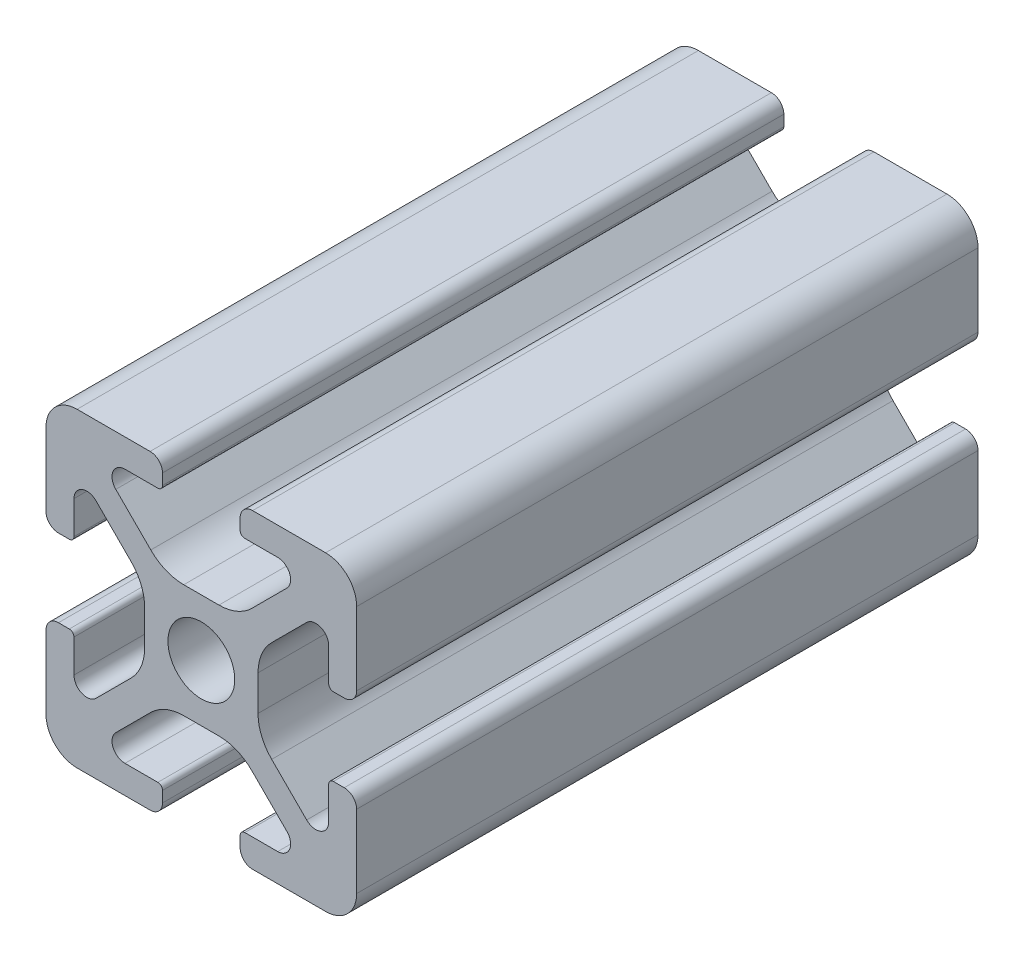
SolidWorks part; units mm, degrees
material "Alliage 1060"
ref_plane "Plan de face" through (0, 0, 0) normal (0, 0, 1) x (1, 0, 0)
ref_plane "Plan de dessus" through (0, 0, 0) normal (0, 1, 0) x (1, 0, 0)
ref_plane "Plan de droite" through (0, 0, 0) normal (1, 0, 0) x (0, 0, -1)
ref_plane "Plan1" through (0, 0, 0) normal (0, 0, -1) x (-1, 0, 0)
sketch "Esquisse1" plane through (0, 0, 0) normal (0, 0, -1) x (-1, 0, 0)
  line L0 (-18, 0) -> (-13.3, 0)
  line L1 (-12.8, 1.8) -> (-14.9184, 1.8)
  line L2 (-15.5064, 3.2196) -> (-13.2547, 5.4713)
  line L3 (-11.1334, 6.35) -> (-8.8666, 6.35)
  line L4 (-6.7453, 5.4713) -> (-4.4936, 3.2196)
  line L5 (-5.0816, 1.8) -> (-7.2, 1.8)
  line L6 (-6.7, 0) -> (-2, 0)
  line L7 (0, 2) -> (0, 6.7)
  line L8 (-1.8, 7.2) -> (-1.8, 5.0816)
  line L9 (-3.2196, 4.4936) -> (-5.4713, 6.7453)
  line L10 (-6.35, 8.8666) -> (-6.35, 11.1334)
  line L11 (-5.4713, 13.2547) -> (-3.2196, 15.5064)
  line L12 (-1.8, 14.9184) -> (-1.8, 12.8)
  line L13 (0, 13.3) -> (0, 18)
  line L14 (-2, 20) -> (-6.7, 20)
  line L15 (-7.2, 18.2) -> (-5.0816, 18.2)
  line L16 (-4.4936, 16.7804) -> (-6.7453, 14.5287)
  line L17 (-8.8666, 13.65) -> (-11.1334, 13.65)
  line L18 (-13.2547, 14.5287) -> (-15.5064, 16.7804)
  line L19 (-14.9184, 18.2) -> (-12.8, 18.2)
  line L20 (-13.3, 20) -> (-18, 20)
  line L21 (-20, 18) -> (-20, 13.3)
  line L22 (-16.7804, 15.5064) -> (-14.5287, 13.2547)
  line L23 (-13.65, 11.1334) -> (-13.65, 8.8666)
  line L24 (-14.5287, 6.7453) -> (-16.7804, 4.4936)
  line L25 (-18.2, 5.0816) -> (-18.2, 7.2)
  line L26 (-20, 6.7) -> (-20, 2)
  arc A0 (-20, 2) -> (-18, 0) centre (-18, 2) ccw
  arc A1 (-13.3, 0) -> (-12.5, 0.8) centre (-13.3, 0.8) ccw
  arc A2 (-12.5, 1.5) -> (-12.8, 1.8) centre (-12.8, 1.5) ccw
  arc A3 (-14.9184, 1.8) -> (-15.5064, 3.2196) centre (-14.9184, 2.6316) cw
  arc A4 (-13.2547, 5.4713) -> (-11.1334, 6.35) centre (-11.1334, 3.35) cw
  arc A5 (-8.8666, 6.35) -> (-6.7453, 5.4713) centre (-8.8666, 3.35) cw
  arc A6 (-4.4936, 3.2196) -> (-5.0816, 1.8) centre (-5.0816, 2.6316) cw
  arc A7 (-7.2, 1.8) -> (-7.5, 1.5) centre (-7.2, 1.5) ccw
  arc A8 (-7.5, 0.8) -> (-6.7, 0) centre (-6.7, 0.8) ccw
  arc A9 (-2, 0) -> (0, 2) centre (-2, 2) ccw
  arc A10 (0, 6.7) -> (-0.8, 7.5) centre (-0.8, 6.7) ccw
  arc A11 (-1.5, 7.5) -> (-1.8, 7.2) centre (-1.5, 7.2) ccw
  arc A12 (-1.8, 5.0816) -> (-3.2196, 4.4936) centre (-2.6316, 5.0816) cw
  arc A13 (-5.4713, 6.7453) -> (-6.35, 8.8666) centre (-3.35, 8.8666) cw
  arc A14 (-6.35, 11.1334) -> (-5.4713, 13.2547) centre (-3.35, 11.1334) cw
  arc A15 (-3.2196, 15.5064) -> (-1.8, 14.9184) centre (-2.6316, 14.9184) cw
  arc A16 (-1.8, 12.8) -> (-1.5, 12.5) centre (-1.5, 12.8) ccw
  arc A17 (-0.8, 12.5) -> (0, 13.3) centre (-0.8, 13.3) ccw
  arc A18 (0, 18) -> (-2, 20) centre (-2, 18) ccw
  arc A19 (-6.7, 20) -> (-7.5, 19.2) centre (-6.7, 19.2) ccw
  arc A20 (-7.5, 18.5) -> (-7.2, 18.2) centre (-7.2, 18.5) ccw
  arc A21 (-5.0816, 18.2) -> (-4.4936, 16.7804) centre (-5.0816, 17.3684) cw
  arc A22 (-6.7453, 14.5287) -> (-8.8666, 13.65) centre (-8.8666, 16.65) cw
  arc A23 (-11.1334, 13.65) -> (-13.2547, 14.5287) centre (-11.1334, 16.65) cw
  arc A24 (-15.5064, 16.7804) -> (-14.9184, 18.2) centre (-14.9184, 17.3684) cw
  arc A25 (-12.8, 18.2) -> (-12.5, 18.5) centre (-12.8, 18.5) ccw
  arc A26 (-12.5, 19.2) -> (-13.3, 20) centre (-13.3, 19.2) ccw
  arc A27 (-18, 20) -> (-20, 18) centre (-18, 18) ccw
  arc A28 (-20, 13.3) -> (-19.2, 12.5) centre (-19.2, 13.3) ccw
  arc A29 (-18.5, 12.5) -> (-18.2, 12.8) centre (-18.5, 12.8) ccw
  arc A30 (-18.2, 14.9184) -> (-16.7804, 15.5064) centre (-17.3684, 14.9184) cw
  arc A31 (-14.5287, 13.2547) -> (-13.65, 11.1334) centre (-16.65, 11.1334) cw
  arc A32 (-13.65, 8.8666) -> (-14.5287, 6.7453) centre (-16.65, 8.8666) cw
  arc A33 (-16.7804, 4.4936) -> (-18.2, 5.0816) centre (-17.3684, 5.0816) cw
  arc A34 (-18.2, 7.2) -> (-18.5, 7.5) centre (-18.5, 7.2) ccw
  arc A35 (-19.2, 7.5) -> (-20, 6.7) centre (-19.2, 6.7) ccw
  circle A36 centre (-10, 10) radius 2.15
  spline S0 degree 1 poles (-12.5, 1.5) (-12.5, 0.8) knots 0 0 0.7 0.7
  spline S1 degree 1 poles (-7.5, 0.8) (-7.5, 1.5) knots 0 0 0.7 0.7
  spline S2 degree 1 poles (-1.5, 7.5) (-0.8, 7.5) knots 0 0 0.7 0.7
  spline S3 degree 1 poles (-0.8, 12.5) (-1.5, 12.5) knots 0 0 0.7 0.7
  spline S4 degree 1 poles (-7.5, 18.5) (-7.5, 19.2) knots 0 0 0.7 0.7
  spline S5 degree 1 poles (-12.5, 19.2) (-12.5, 18.5) knots 0 0 0.7 0.7
  spline S6 degree 1 poles (-18.5, 12.5) (-19.2, 12.5) knots 0 0 0.7 0.7
  spline S7 degree 1 poles (-18.2, 14.9184) (-18.2, 12.8) knots 0 0 2.118424 2.118424
  spline S8 degree 1 poles (-19.2, 7.5) (-18.5, 7.5) knots 0 0 0.7 0.7
extrude "Extrusion1" add sketch "Esquisse1" against normal blind 40
